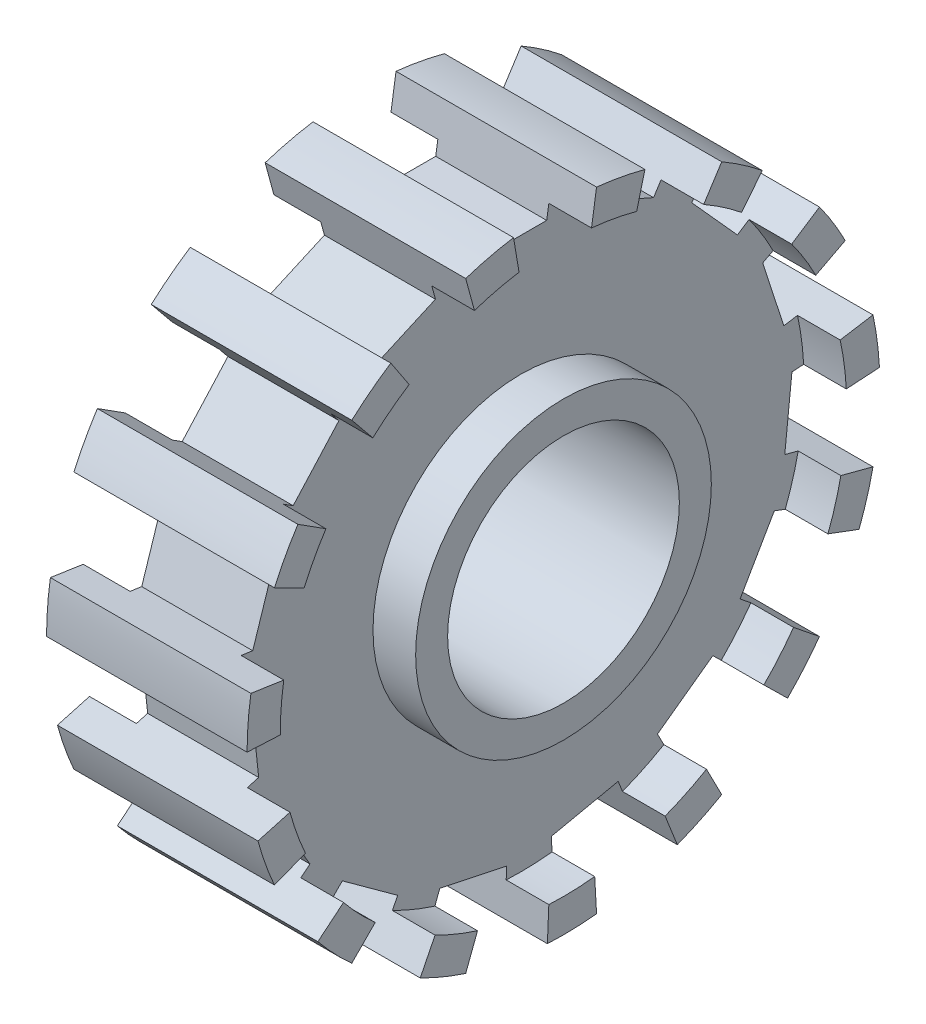
SolidWorks part; units mm, degrees
ref_plane "Front Plane" through (0, 0, 0) normal (0, 0, 1) x (1, 0, 0)
ref_plane "Top Plane" through (0, 0, 0) normal (0, 1, 0) x (1, 0, 0)
ref_plane "Right Plane" through (0, 0, 0) normal (1, 0, 0) x (0, 0, -1)
sketch "Sketch1" plane through (0, 0, 0) normal (0, 0, 1) x (1, 0, 0)
  line L0 (0, 0) -> (-10, 0) construction
  line L1 (0, 5.7784) -> (-10, 5.7784)
  line L2 (-10, 5.7784) -> (-10, 7.373)
  line L3 (-10, 7.373) -> (-7.6624, 7.373)
  line L4 (-7.6624, 7.373) -> (-7.6624, 14.1222)
  line L5 (-7.6624, 14.1222) -> (-10, 14.1222)
  line L6 (-10, 14.1222) -> (-10, 15.7784)
  line L7 (-10, 15.7784) -> (0, 15.7784)
  line L8 (0, 15.7784) -> (0, 14.1222)
  line L9 (0, 14.1222) -> (-2.1265, 14.1222)
  line L10 (-2.1265, 14.1222) -> (-2.1265, 7.373)
  line L11 (-2.1265, 7.373) -> (0, 7.373)
  line L12 (0, 7.373) -> (0, 5.7784)
  point P9 (0, 0)
  point P16 (0, 0)
  dimension "D1" = 15.7784
  dimension "D2" = 10
  dimension "D3" = 10
  dimension "D4" = 5.5359
revolve "Revolve1" add sketch "Sketch1" angle 360 about L0
sketch "Sketch2" plane through (0, 0, 0) normal (1, 0, 0) x (0, 0, -1)
  line L0 (-2.7763, 17.2844) -> (-2.1197, 13.3696)
  line L1 (-2.1197, 13.3696) -> (1.2901, 13.3696)
  line L2 (1.2901, 13.3696) -> (1.8962, 17.2844)
  line L3 (1.8962, 17.2844) -> (-2.7763, 17.2844)
extrude "Cut-Extrude3" cut sketch "Sketch2" against normal blind 16
pattern_circular "CirPattern1" count 15 over 360 about axis through (0, 0, 0) along (1, 0, 0) of "Cut-Extrude3"
